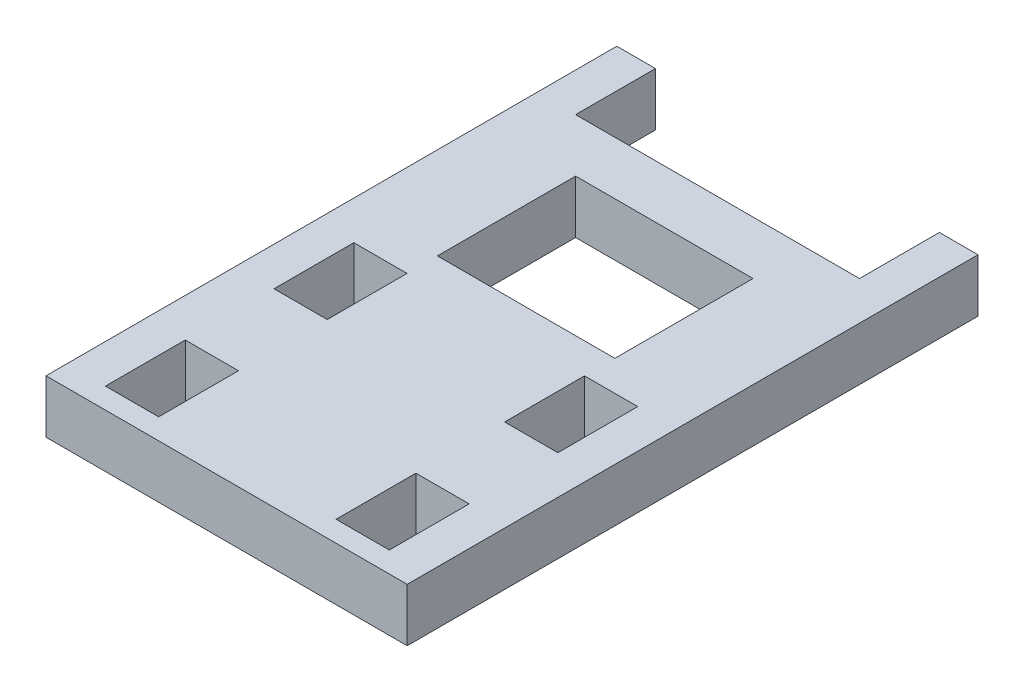
SolidWorks part; units mm, degrees
ref_plane "Front Plane" through (0, 0, 0) normal (0, 0, 1) x (1, 0, 0)
ref_plane "Top Plane" through (0, 0, 0) normal (0, 1, 0) x (1, 0, 0)
ref_plane "Right Plane" through (0, 0, 0) normal (1, 0, 0) x (0, 0, -1)
sketch "Sketch1" plane through (0, 0, 0) normal (0, 1, 0) x (1, 0, 0)
  line L0 (2.378, 4.431) -> (2.378, -5.569) construction
  line L1 (8.378, 13.431) -> (8.378, 38.431) construction
  line L2 (-27.9778, 17.5799) -> (-27.9778, -16.91)
  line L3 (-27.9778, -16.91) -> (12.7339, -16.91)
  line L4 (12.7339, 17.5799) -> (12.7339, -16.91)
  line L5 (-27.9778, 17.5799) -> (-27.9778, 38.431)
  line L6 (-23.622, 38.431) -> (8.378, 38.431)
  line L15 (2.378, 13.431) -> (8.378, 13.431)
  line L16 (2.378, 13.431) -> (2.378, 4.431)
  line L17 (2.378, 4.431) -> (8.378, 4.431)
  line L18 (8.378, 13.431) -> (8.378, 4.431)
  line L19 (2.378, -5.569) -> (8.378, -5.569)
  line L20 (2.378, -5.569) -> (2.378, -14.569)
  line L21 (2.378, -14.569) -> (8.378, -14.569)
  line L22 (8.378, -5.569) -> (8.378, -14.569)
  line L23 (-23.622, 4.431) -> (-17.622, 4.431)
  line L24 (-23.622, 4.431) -> (-23.622, 13.431)
  line L25 (-23.622, 13.431) -> (-17.622, 13.431)
  line L26 (-17.622, 4.431) -> (-17.622, 13.431)
  line L27 (-23.622, -5.569) -> (-17.622, -5.569)
  line L28 (-23.622, -5.569) -> (-23.622, -14.569)
  line L29 (-23.622, -14.569) -> (-17.622, -14.569)
  line L30 (-17.622, -5.569) -> (-17.622, -14.569)
  line L31 (12.7339, 38.431) -> (12.7339, 17.5799)
  line L32 (-17.622, 16.8518) -> (2.378, 16.8518)
  line L33 (-17.622, 16.8518) -> (-17.622, 32.431)
  line L34 (-17.622, 32.431) -> (2.378, 32.431)
  line L35 (2.378, 16.8518) -> (2.378, 32.431)
  line L36 (-17.622, 4.431) -> (2.378, 4.431) construction
  line L37 (2.378, 32.431) -> (2.378, 38.431) construction
  line L38 (-27.9778, 38.431) -> (-27.9778, 47.431)
  line L39 (-27.9778, 47.431) -> (-23.622, 47.431)
  line L40 (-23.622, 38.431) -> (-23.622, 47.431)
  line L42 (12.7339, 38.431) -> (12.7339, 47.431)
  line L43 (12.7339, 47.431) -> (8.378, 47.431)
  line L44 (8.378, 38.431) -> (8.378, 47.431)
  point P0 (0, 0)
extrude "Boss-Extrude1" add sketch "Sketch1" along normal blind 6
